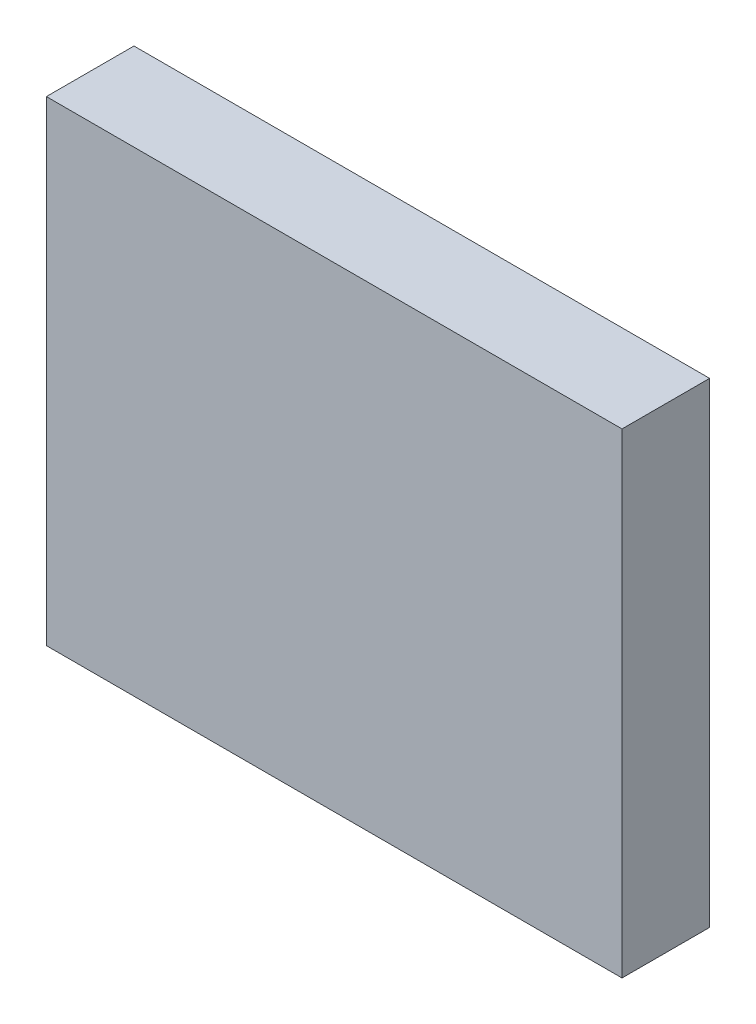
SolidWorks part; units mm, degrees
material "Zinc AC43A (Zn-4Al-2.5Cu-0.04Mg; Number 2 Die Casting Alloy; Zamak 2), Die Cast"
ref_plane "Front Plane" through (0, 0, 0) normal (0, 0, 1) x (1, 0, 0)
ref_plane "Top Plane" through (0, 0, 0) normal (0, 1, 0) x (1, 0, 0)
ref_plane "Right Plane" through (0, 0, 0) normal (1, 0, 0) x (0, 0, -1)
sketch "Sketch1" plane through (0, 0, 0) normal (0, 0, 1) x (1, 0, 0)
  line L1 (11.5, -9.5) -> (-11.5, -9.5)
  line L2 (11.5, -9.5) -> (11.5, 9.5)
  line L3 (11.5, 9.5) -> (-11.5, 9.5)
  line L4 (-11.5, -9.5) -> (-11.5, 9.5)
  line L5 (11.5, -9.5) -> (-11.5, 9.5) construction
  line L6 (11.5, 9.5) -> (-11.5, -9.5) construction
  point P0 (0, 0)
  dimension "D1" = 19
  dimension "D2" = 23
extrude "Boss-Extrude1" add sketch "Sketch1" along normal mid plane 3.5
